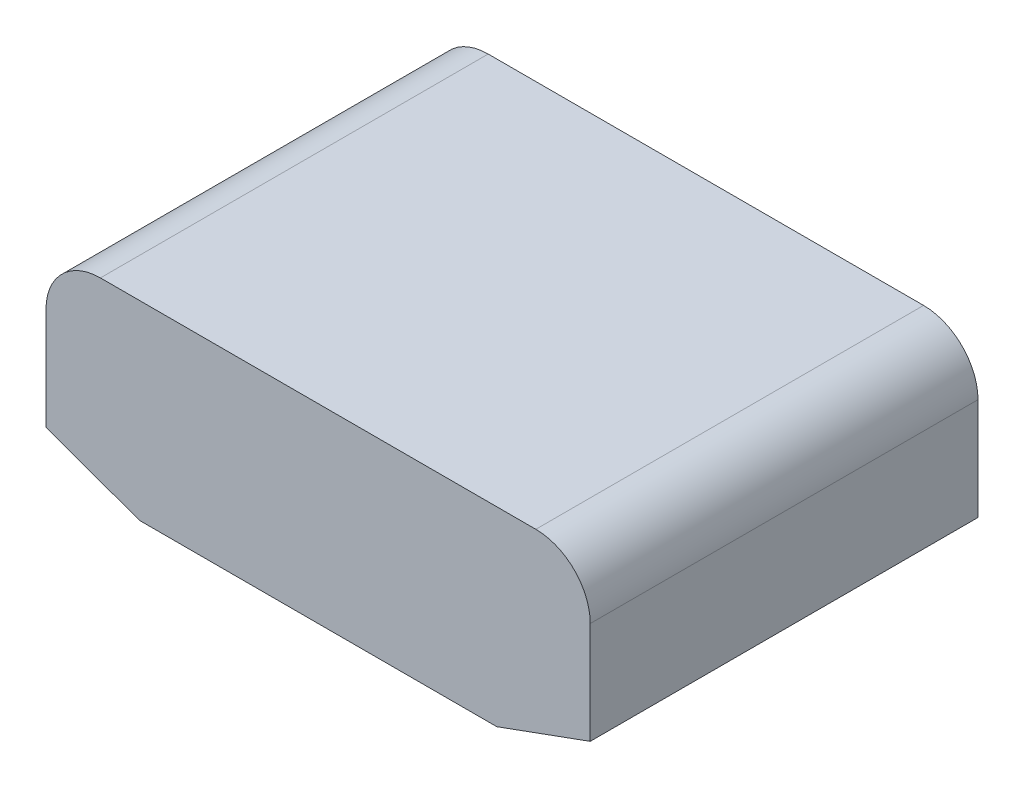
SolidWorks part; units mm, degrees
ref_plane "Спереди" through (0, 0, 0) normal (0, 0, 1) x (1, 0, 0)
ref_plane "Сверху" through (0, 0, 0) normal (0, 1, 0) x (1, 0, 0)
ref_plane "Справа" through (0, 0, 0) normal (1, 0, 0) x (0, 0, -1)
sketch "Эскиз1" plane through (0, 0, 0) normal (0, 0, 1) x (1, 0, 0)
  line L5 (-7.2892, 2.8) -> (0.7108, 2.8)
  line L6 (0.7108, 2.8) -> (0.7108, 0)
  line L7 (0.7108, 0) -> (-7.2892, 0)
  line L9 (-7.2892, 1.8) -> (0.7108, 1.8)
  line L10 (-7.2892, 2.8) -> (-7.2892, 0)
  dimension "D1" = 2.8
  dimension "D3" = 1
extrude "Бобышка-Вытянуть1" add sketch "Эскиз1" along normal blind 5.7 contours L5 L10 L9 L6 | L9 L10 L7 L6
fillet "Скругление1" radius 0.8 2 edges at (-7.2892, 2.8, 2.85) (0.7108, 2.8, 2.85)
chamfer "Фаска1" distance 0.5 angle 70 2 edges at (0.7108, 0, 2.85) (-7.2892, 0, 2.85)
sketch "Эскиз2" plane through (0, 0, 0) normal (0, 0, -1) x (-1, 0, 0)
  line L7 (5.8449, 1.7312) -> (1.144, 1.7312)
  line L8 (5.8449, 1.7312) -> (5.8449, 1.1194)
  line L9 (5.8449, 1.1194) -> (1.144, 1.1194)
  line L10 (1.144, 1.7312) -> (1.144, 1.1194)
  line L12 (-0.3108, 2) -> (-0.3108, 0.7801)
  line L13 (-0.3108, 0.7801) -> (0.7334, 0.4)
  line L14 (0.7334, 0.4) -> (5.8449, 0.4)
  line L15 (5.8449, 0.4) -> (6.8892, 0.7801)
  line L16 (6.8892, 0.7801) -> (6.8892, 2)
  line L17 (6.4892, 2.4) -> (0.0892, 2.4)
  line L18 (-0.3108, 2) -> (-0.3108, 0.7801)
  line L19 (-0.3108, 0.7801) -> (0.7334, 0.4)
  line L20 (0.7334, 0.4) -> (5.8449, 0.4)
  line L21 (5.8449, 0.4) -> (6.8892, 0.7801)
  line L22 (6.8892, 0.7801) -> (6.8892, 2)
  line L23 (6.4892, 2.4) -> (0.0892, 2.4)
  arc A4 (6.8892, 2) -> (6.4892, 2.4) centre (6.4892, 2) ccw
  arc A5 (0.0892, 2.4) -> (-0.3108, 2) centre (0.0892, 2) ccw
  arc A6 (6.8892, 2) -> (6.4892, 2.4) centre (6.4892, 2) ccw
  arc A7 (0.0892, 2.4) -> (-0.3108, 2) centre (0.0892, 2) ccw
  dimension "D1" = 0.4
extrude "Вырез-Вытянуть1" cut sketch "Эскиз2" against normal blind 5
